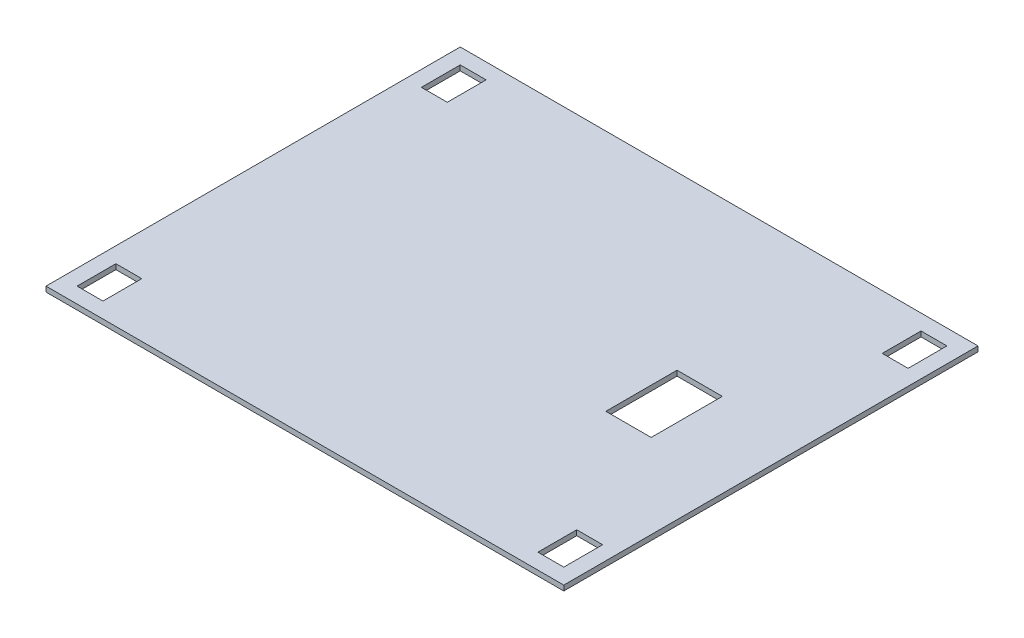
SolidWorks part; units mm, degrees
ref_plane "Front Plane" through (0, 0, 0) normal (0, 0, 1) x (1, 0, 0)
ref_plane "Top Plane" through (0, 0, 0) normal (0, 1, 0) x (1, 0, 0)
ref_plane "Right Plane" through (0, 0, 0) normal (1, 0, 0) x (0, 0, -1)
sketch "Sketch1" plane through (0, 0, 0) normal (0, 1, 0) x (1, 0, 0)
  line L1 (-63.5, 50.8) -> (63.5, 50.8)
  line L2 (-63.5, 50.8) -> (-63.5, -50.8)
  line L3 (-63.5, -50.8) -> (63.5, -50.8)
  line L4 (63.5, 50.8) -> (63.5, -50.8)
  dimension "D1" = 127
  dimension "D2" = 101.6
  dimension "D3" = 50.8
  dimension "D4" = 63.5
extrude "Boss-Extrude1" add sketch "Sketch1" along normal blind 1.27
sketch "Sketch2" plane through (0, 1.27, 0) normal (0, 1, 0) x (1, 0, 0)
  line L0 (-63.5, 50.8) -> (-63.5, -50.8) construction
  line L1 (-59.69, 46.99) -> (-53.34, 46.99)
  line L2 (-59.69, 46.99) -> (-59.69, 37.465)
  line L3 (-59.69, 37.465) -> (-53.34, 37.465)
  line L4 (-53.34, 46.99) -> (-53.34, 37.465)
  line L5 (63.5, 50.8) -> (-63.5, 50.8) construction
  line L6 (0, -0.6985) -> (0, 0.6985) construction
  line L7 (53.34, 46.99) -> (53.34, 37.465)
  line L8 (59.69, 46.99) -> (53.34, 46.99)
  line L9 (59.69, 46.99) -> (59.69, 37.465)
  line L10 (59.69, 37.465) -> (53.34, 37.465)
  line L11 (-0.6985, 0) -> (0.6985, 0) construction
  line L12 (59.69, -37.465) -> (53.34, -37.465)
  line L13 (53.34, -46.99) -> (53.34, -37.465)
  line L14 (59.69, -46.99) -> (53.34, -46.99)
  line L15 (59.69, -46.99) -> (59.69, -37.465)
  line L16 (-53.34, -46.99) -> (-53.34, -37.465)
  line L17 (-59.69, -46.99) -> (-53.34, -46.99)
  line L18 (-59.69, -46.99) -> (-59.69, -37.465)
  line L19 (-59.69, -37.465) -> (-53.34, -37.465)
  point P4 (-59.69, 42.2275)
  dimension "D1" = 6.35
  dimension "D2" = 9.525
  dimension "D3" = 3.81
  dimension "D4" = 3.81
extrude "Cut-Extrude1" cut sketch "Sketch2" against normal up to next
sketch "Sketch3" plane through (0, 1.27, 0) normal (0, 1, 0) x (1, 0, 0)
  line L1 (42.8625, -8.7312) -> (31.75, -8.7312)
  line L2 (42.8625, -8.7312) -> (42.8625, 8.7313)
  line L3 (42.8625, 8.7313) -> (31.75, 8.7313)
  line L4 (31.75, -8.7312) -> (31.75, 8.7313)
  dimension "D1" = 11.1125
  dimension "D2" = 17.4625
  dimension "D3" = 31.75
  dimension "D4" = 8.7312
extrude "Cut-Extrude2" cut sketch "Sketch3" against normal up to next
